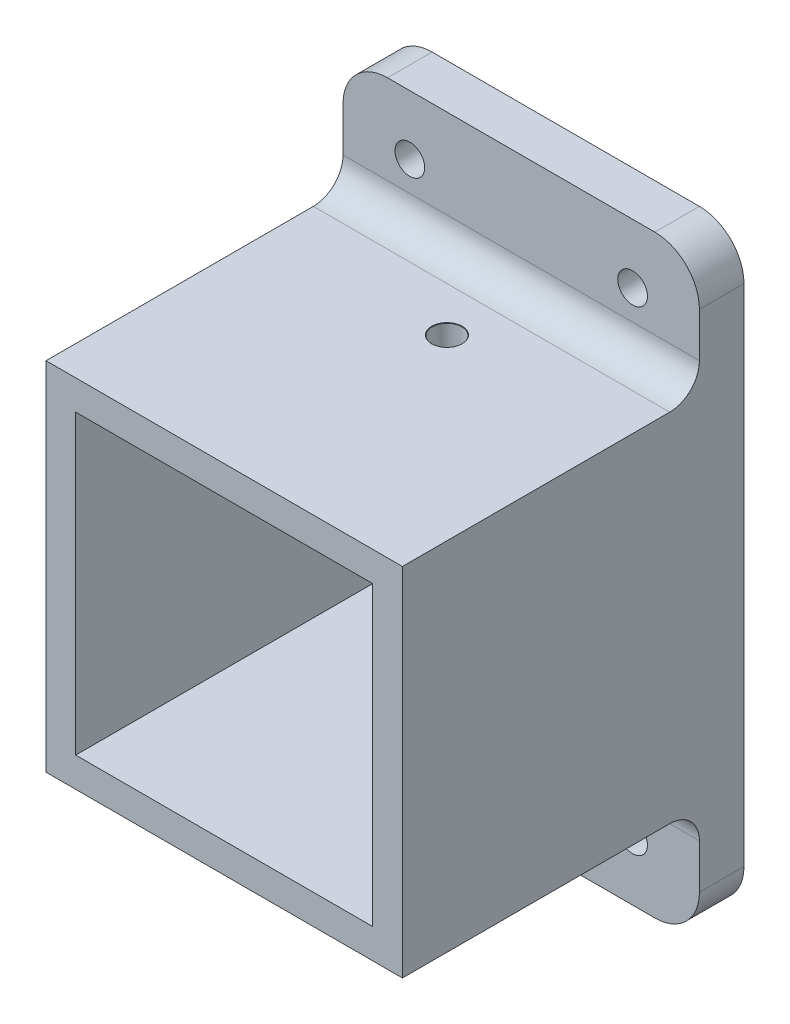
SolidWorks part; units mm, degrees
material "Rubber"
ref_plane "Front Plane" through (0, 0, 0) normal (1, 0, 0) x (0, 1, 0)
ref_plane "Top Plane" through (0, 0, 0) normal (0, 0, 1) x (0, 1, 0)
ref_plane "Right Plane" through (0, 0, 0) normal (0, 1, 0) x (-1, 0, 0)
sketch "Sketch1" plane through (0, 0, 0) normal (0, 0, 1) x (0, 1, 0)
  line L0 (-10, 10) -> (10, 10)
  line L1 (-12, 12) -> (12, 12)
  line L2 (-12, 12) -> (-12, -12)
  line L3 (-12, -12) -> (12, -12)
  line L4 (12, 12) -> (12, -12)
  line L5 (10, 10) -> (10, -10)
  line L6 (-10, -10) -> (10, -10)
  line L7 (-10, 10) -> (-10, -10)
  point P5 (-12, 0)
  point P6 (0, 12)
  dimension "D1" = 24
  dimension "D2" = 24
  dimension "D3" = 0
  dimension "D4" = 0
  dimension "D5" = 2
extrude "Boss-Extrude1" add sketch "Sketch1" along normal blind 20
sketch "Sketch2" plane through (0, 0, 0) normal (0, 0, -1) x (1, 0, 0)
  line L1 (12, 20) -> (-12, 20)
  line L2 (12, 20) -> (12, -20)
  line L3 (12, -20) -> (-12, -20)
  line L4 (12, 12) -> (-12, 12)
  line L5 (-12, 12) -> (-12, -12)
  line L6 (-12, -12) -> (12, -12)
  line L7 (12, -12) -> (12, 12)
  line L8 (12, 12) -> (-12, 12)
  line L9 (-12, 12) -> (-12, -12)
  line L10 (-12, -12) -> (12, -12)
  line L11 (12, -12) -> (12, 12)
  line L12 (-12, 20) -> (-12, -20)
  point P8 (12, 0)
  line M9 (12, 12) -> (-12, 12)
  line M10 (-12, 12) -> (-12, -12)
  line M11 (-12, -12) -> (12, -12)
  line M12 (12, -12) -> (12, 12)
  line M13 (-10, 10) -> (10, 10)
  line M14 (10, 10) -> (10, -10)
  line M15 (10, -10) -> (-10, -10)
  line M16 (-10, -10) -> (-10, 10)
  dimension "D2" = 0
  dimension "D3" = 0
  dimension "D4" = 0
  dimension "D5" = 40
  dimension "D1" = 0
extrude "Boss-Extrude2" add sketch "Sketch2" along normal blind 3 contours L1 L12 L2 M9 | L12 L3 L2 M11 | M12 M9 M10 M11 M16 M13 M14 M15 | M13 M16 M15 M14
sketch "Sketch3" plane through (0, 0, -3) normal (0, 0, -1) x (1, 0, 0)
  line L1 (-7.5, 16) -> (7.5, 16)
  line L2 (-7.5, 16) -> (-7.5, -16)
  line L3 (-7.5, -16) -> (7.5, -16)
  line L4 (12, 20) -> (-12, 20)
  line L5 (-12, 20) -> (-12, -20)
  line L6 (-12, -20) -> (12, -20)
  line L7 (12, -20) -> (12, 20)
  line L8 (12, 20) -> (-12, 20)
  line L9 (-12, 20) -> (-12, -20)
  line L10 (-12, -20) -> (12, -20)
  line L11 (12, -20) -> (12, 20)
  line L12 (7.5, 16) -> (7.5, -16)
  point P8 (0, 16)
  point P9 (0, 20)
  point P10 (-7.5, 0)
  point P11 (-12, 0)
  point P12 (-27.5245, 46.8224)
  point P13 (-7.5, 16)
  point P14 (7.5, 16)
  point P15 (-7.5, -16)
  point P16 (7.5, -16)
  dimension "D2" = 0
  dimension "D3" = 0
  dimension "D4" = 15
  dimension "D5" = 32
  dimension "D1" = 0
hole_wizard "Ø2.0mm Dowel Hole1" positions "Sketch3" profile "Sketch4" hole size "Ø2.0" standard "IS" end condition through all
sketch "Sketch4" plane through (7.5, 16, -3) normal (1, 0, 0) x (0, 1, 0)
  line L0 (0, 0) -> (0, 23)
  line L1 (0, 23) -> (1, 23)
  line L2 (1, 23) -> (1, 0.025)
  line L3 (1, 0.025) -> (1.025, 0)
  line L5 (1.025, 0) -> (0, 0)
  line L6 (-1, 0.025) -> (-1.025, 0) construction
  line L11 (0, -6.35) -> (0, 107.95) construction
  dimension "Thru Hole Dia." = 2
  dimension "Thru Hole Depth" = 23
  dimension "Near C'Sink Dia." = 2.05
  dimension "Near C'Sink Angle" = 90
sketch "Sketch5" plane through (0, 12, 0) normal (0, 1, 0) x (-1, 0, 0)
  point P0 (0, 5)
  dimension "D1" = 0
  dimension "D2" = 5
hole_wizard "Ø2.0mm Dowel Hole2" positions "Sketch5" profile "Sketch6" hole size "Ø2.0" standard "IS" end condition through all
sketch "Sketch6" plane through (0, 12, 5) normal (1, 0, 0) x (0, 0, 1)
  line L0 (0, 0) -> (0, 32)
  line L1 (0, 32) -> (1, 32)
  line L2 (1, 32) -> (1, 0.025)
  line L3 (1, 0.025) -> (1.025, 0)
  line L5 (1.025, 0) -> (0, 0)
  line L6 (-1, 0.025) -> (-1.025, 0) construction
  line L11 (0, -6.35) -> (0, 107.95) construction
  dimension "Thru Hole Dia." = 2
  dimension "Thru Hole Depth" = 32
  dimension "Near C'Sink Dia." = 2.05
  dimension "Near C'Sink Angle" = 90
fillet "Fillet1" radius 3 4 edges at (-12, -20, -1.5) (12, -20, -1.5) (-12, 20, -1.5) (12, 20, -1.5)
fillet "Fillet2" radius 2 2 edges at (0, 12, 0) (0, -12, 0)
